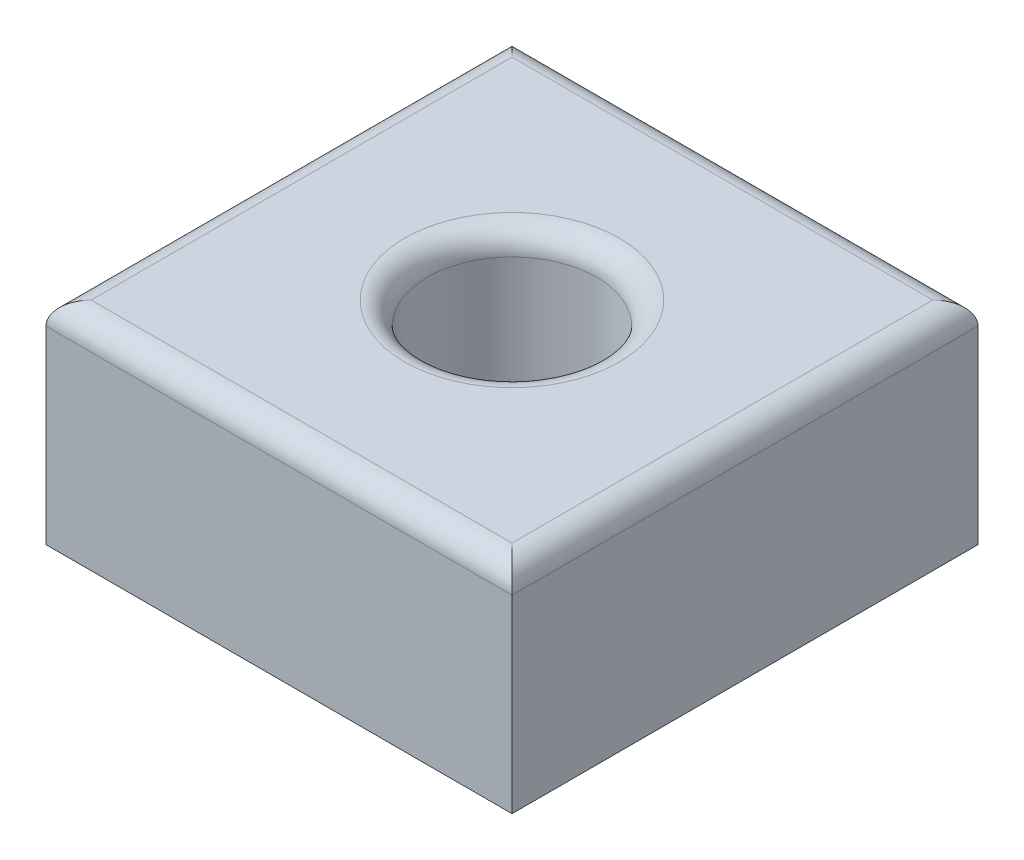
SolidWorks part; units mm, degrees
ref_plane "Front Plane" through (0, 0, 0) normal (0, 0, 1) x (1, 0, 0)
ref_plane "Top Plane" through (0, 0, 0) normal (0, 1, 0) x (1, 0, 0)
ref_plane "Right Plane" through (0, 0, 0) normal (1, 0, 0) x (0, 0, -1)
sketch "Sketch1" plane through (0, 0, 0) normal (0, 1, 0) x (1, 0, 0)
  line L1 (-26.1938, 26.1937) -> (26.1937, 26.1937)
  line L2 (-26.1938, 26.1937) -> (-26.1938, -26.1937)
  line L3 (-26.1938, -26.1937) -> (26.1937, -26.1937)
  line L4 (26.1937, 26.1937) -> (26.1937, -26.1937)
  circle A0 centre (0, 0) radius 9.525
  point P6 (0, 26.1937)
  point P7 (-26.1938, 0)
  dimension "D1" = 52.3875
  dimension "D2" = 52.3875
extrude "Boss-Extrude1" add sketch "Sketch1" along normal blind 23.8125
fillet "Fillet1" radius 2.54 5 edges at (0, 23.8125, 9.525) (0, 23.8125, -26.1937) (26.1937, 23.8125, 0) (0, 23.8125, 26.1937) (-26.1938, 23.8125, 0)
